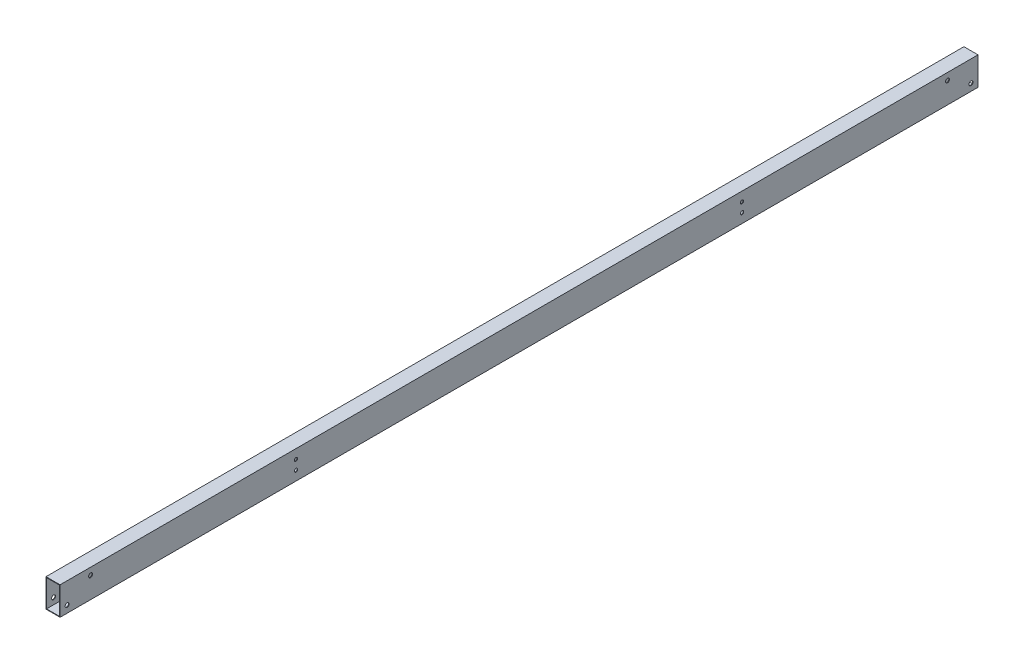
SolidWorks part; units mm, degrees
ref_plane "Front Plane" through (0, 0, 0) normal (0, 0, 1) x (1, 0, 0)
ref_plane "Top Plane" through (0, 0, 0) normal (0, 1, 0) x (1, 0, 0)
ref_plane "Right Plane" through (0, 0, 0) normal (1, 0, 0) x (0, 0, -1)
sketch "Sketch1" plane through (0, 0, 0) normal (0, 0, 1) x (1, 0, 0)
  line L0 (1.2, 58.8) -> (28.8, 58.8)
  line L1 (0, 0) -> (30, 0)
  line L2 (0, 0) -> (0, 60)
  line L3 (0, 60) -> (30, 60)
  line L4 (30, 0) -> (30, 60)
  line L5 (28.8, 1.2) -> (28.8, 58.8)
  line L6 (1.2, 1.2) -> (28.8, 1.2)
  line L7 (1.2, 1.2) -> (1.2, 58.8)
  dimension "D1" = 30
  dimension "D2" = 60
  dimension "D3" = 1.2
extrude "Boss-Extrude1" add sketch "Sketch1" along normal blind 1955
sketch "Sketch4" plane through (30, 0, 0) normal (1, 0, 0) x (0, 0, -1)
  line L0 (-977.5, 60) -> (-977.5, 0) construction
  line L1 (-1955, 60) -> (0, 60) construction
  line L2 (-1955, 0) -> (0, 0) construction
  line L4 (-502.5, 20) -> (-1452.5, 20) construction
  line L5 (-502.5, 20) -> (-502.5, 40) construction
  line L6 (-502.5, 40) -> (-1452.5, 40) construction
  line L7 (-1452.5, 20) -> (-1452.5, 40) construction
  line L8 (-502.5, 20) -> (-1452.5, 40) construction
  line L9 (-502.5, 40) -> (-1452.5, 20) construction
  circle A0 centre (-1452.5, 40) radius 3.5
  circle A1 centre (-1452.5, 20) radius 3.5
  circle A2 centre (-502.5, 40) radius 3.5
  circle A3 centre (-502.5, 20) radius 3.5
  point P6 (-977.5, 30)
  dimension "D3" = 7
  dimension "D1" = 20
  dimension "D2" = 950
extrude "Cut-Extrude3" cut sketch "Sketch4" against normal through all
sketch "Sketch5" plane through (30, 0, 0) normal (1, 0, 0) x (0, 0, -1)
  line L0 (0, 0) -> (0, 60) construction
  line L1 (-1955, 0) -> (0, 0) construction
  line L2 (-1955, 60) -> (0, 60) construction
  line L3 (-1955, 0) -> (-1955, 60) construction
  circle A0 centre (-15, 15) radius 4.25
  circle A1 centre (-65, 45) radius 4.25
  circle A2 centre (-1890, 45) radius 4.25
  circle A3 centre (-1940, 15) radius 4.25
  dimension "D1" = 8.5
  dimension "D2" = 15
  dimension "D3" = 15
  dimension "D4" = 15
  dimension "D5" = 50
  dimension "D7" = 15
  dimension "D8" = 50
  dimension "D9" = 15
  dimension "D6" = 15
extrude "Cut-Extrude4" cut sketch "Sketch5" against normal through all
